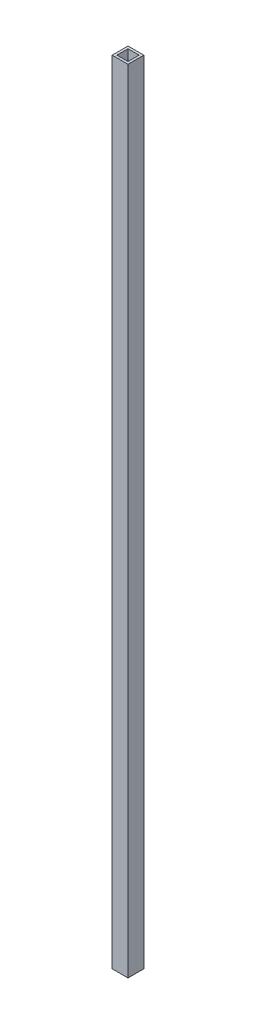
SolidWorks part; units mm, degrees
material "6061 合金"
ref_plane "前视基准面" through (0, 0, 0) normal (0, 0, 1) x (1, 0, 0)
ref_plane "上视基准面" through (0, 0, 0) normal (0, 1, 0) x (1, 0, 0)
ref_plane "右视基准面" through (0, 0, 0) normal (1, 0, 0) x (0, 0, -1)
sketch "草图1" plane through (0, 0, 0) normal (0, 1, 0) x (1, 0, 0)
  line L1 (-7, 7) -> (7, 7)
  line L2 (-7, 7) -> (-7, -7)
  line L3 (-7, -7) -> (7, -7)
  line L4 (7, 7) -> (7, -7)
  line L5 (0, -7) -> (0, 7) construction
  line L6 (-7, 0) -> (7, 0) construction
  line L7 (-10, 10) -> (10, 10)
  line L8 (-10, 10) -> (-10, -10)
  line L9 (-10, -10) -> (10, -10)
  line L10 (10, 10) -> (10, -10)
  line L11 (0, -10) -> (0, 10) construction
  line L12 (-10, 0) -> (10, 0) construction
  point P0 (0, 0)
  point P4 (0, 0)
  dimension "D1" = 20
  dimension "D2" = 20
  dimension "D3" = 3
  dimension "D4" = 3
extrude "凸台-拉伸1" add sketch "草图1" along normal blind 1000
